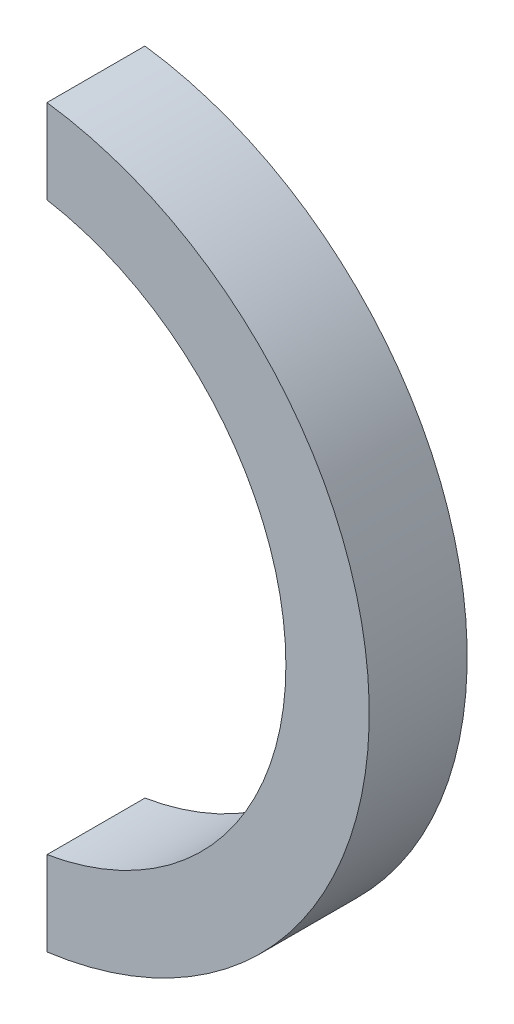
SolidWorks part; units mm, degrees
material "POLYURETHANE (11671)"
ref_plane "Front Plane" through (0, 0, 0) normal (0, 0, 1) x (1, 0, 0)
ref_plane "Top Plane" through (0, 0, 0) normal (0, 1, 0) x (1, 0, 0)
ref_plane "Right Plane" through (0, 0, 0) normal (1, 0, 0) x (0, 0, -1)
sketch "Sketch1" plane through (0, 0, 0) normal (0, 0, 1) x (1, 0, 0)
  line L0 (0, 55.704) -> (0, 71.845) construction
  line L1 (0, -71.845) -> (0, -55.704) construction
  line L2 (0, 55.704) -> (0, -55.704) construction
  line L3 (9.4375, 54.8987) -> (9.4375, 71.2225)
  line L4 (9.4375, -54.8987) -> (9.4375, -71.2225)
  arc A0 (9.4375, -71.2225) -> (9.4375, 71.2225) centre (0, 0) ccw
  arc A1 (9.4375, -54.8987) -> (9.4375, 54.8987) centre (0, 0) ccw
  arc A2 (0, -71.845) -> (9.4375, -71.2225) centre (0, 0) ccw construction
  arc A3 (0, 71.845) -> (9.4375, 71.2225) centre (0, 0) cw construction
  arc A4 (0, -55.704) -> (9.4375, -54.8987) centre (0, 0) ccw construction
  dimension "D2" = 16.141
  dimension "D1" = 71.845
  dimension "D3" = 9.4375
extrude "Boss-Extrude1" add sketch "Sketch1" along normal blind 18.966
equation "\"B1\"=0.037750"
equation "\"B2\"=0.018875"
equation "\"B3\"=0.055704"
equation "\"H1\"=0.029178"
equation "\"H2\"=0.048144"
equation "\"H3\"=0.126925"
equation "\"H4\"=0.145891"
equation "\"T\"=0.005000"
equation "\"L\"=0.026425"
equation "\"bolt_hole_diameter\"=0.003400"
equation "\"D1@Sketch1\"=\"D_strap\"*1000"
equation "\"D2@Sketch1\"=\"pad_t1\"*1000"
equation "\"D3@Sketch1\"=0.5*\"B2\"*1000"
equation "\"spring_arm_hole_pos\"=0.010570"
equation "\"spring_arm_hole_max_diam\"=0.006000"
equation "\"spring_arm_hole_min_diam\"=0.003400"
equation "\"arm_hole_head_height\"=0.001650"
equation "\"H_holes\"=0.008494"
equation "\"D_strap\"=0.071845"
equation "\"clip_hole_D\"=0.003400"
equation "\"clip_hole_y1\"=0.007500"
equation "\"clip_hole_dist\"=0.015000"
equation "\"pad_t1\"=0.016141"
equation "\"pad_t2\"=0.000000"
equation "\"unpad_L1\"=0.067481"
equation "\"D1@Boss-Extrude1\"=(\"H4\"-\"H3\")*1000"
